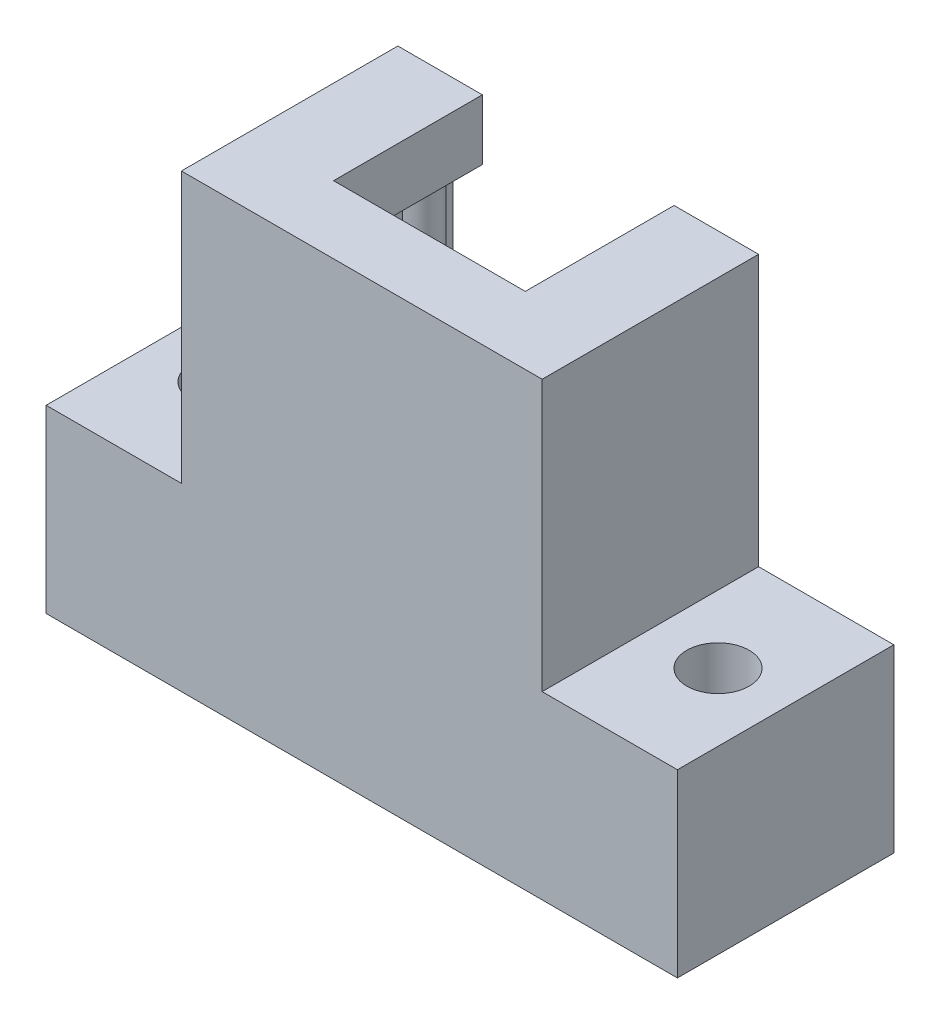
SolidWorks part; units mm, degrees
ref_plane "Front Plane" through (0, 0, 0) normal (0, 0, 1) x (1, 0, 0)
ref_plane "Top Plane" through (0, 0, 0) normal (0, 1, 0) x (1, 0, 0)
ref_plane "Right Plane" through (0, 0, 0) normal (1, 0, 0) x (0, 0, -1)
sketch "Sketch1" plane through (0, 0, 0) normal (0, 1, 0) x (1, 0, 0)
  line L1 (-17.5, -6) -> (17.5, -6)
  line L2 (-17.5, -6) -> (-17.5, 6)
  line L3 (-17.5, 6) -> (17.5, 6)
  line L4 (17.5, -6) -> (17.5, 6)
  line L5 (-17.5, -6) -> (17.5, 6) construction
  line L6 (-17.5, 6) -> (17.5, -6) construction
  point P0 (0, 0)
  dimension "D1" = 35
  dimension "D2" = 12
extrude "Boss-Extrude1" add sketch "Sketch1" along normal blind 10
sketch "Sketch2" plane through (0, 0, 0) normal (0, 1, 0) x (1, 0, 0)
  line L0 (17.5, 6) -> (-17.5, 6) construction
  line L1 (-10, -6) -> (10, -6)
  line L2 (-10, -6) -> (-10, 6)
  line L3 (-10, 6) -> (10, 6)
  line L4 (10, -6) -> (10, 6)
  line L5 (-10, -6) -> (10, 6) construction
  line L6 (-10, 6) -> (10, -6) construction
  point P0 (0, 0)
  dimension "D1" = 20
extrude "Boss-Extrude2" add sketch "Sketch2" along normal blind 25
sketch "Sketch3" plane through (0, 0, 0) normal (0, 1, 0) x (1, 0, 0)
  line L4 (-6.68, 2.615) -> (-6.68, -2.615)
  line L5 (-5.68, -3.615) -> (5.68, -3.615)
  line L6 (6.68, -2.615) -> (6.68, 2.615)
  line L7 (5.68, 3.615) -> (-5.68, 3.615)
  line L8 (-6.68, 2.615) -> (-6.68, -2.615)
  line L9 (-5.68, -3.615) -> (5.68, -3.615)
  line L10 (6.68, -2.615) -> (6.68, 2.615)
  line L11 (5.68, 3.615) -> (-5.68, 3.615)
  arc A4 (-6.68, -2.615) -> (-5.68, -3.615) centre (-5.68, -2.615) ccw
  arc A5 (5.68, -3.615) -> (6.68, -2.615) centre (5.68, -2.615) ccw
  arc A6 (6.68, 2.615) -> (5.68, 3.615) centre (5.68, 2.615) ccw
  arc A7 (-5.68, 3.615) -> (-6.68, 2.615) centre (-5.68, 2.615) ccw
  arc A8 (-6.68, -2.615) -> (-5.68, -3.615) centre (-5.68, -2.615) ccw
  arc A9 (5.68, -3.615) -> (6.68, -2.615) centre (5.68, -2.615) ccw
  arc A10 (6.68, 2.615) -> (5.68, 3.615) centre (5.68, 2.615) ccw
  arc A11 (-5.68, 3.615) -> (-6.68, 2.615) centre (-5.68, 2.615) ccw
  circle A36 centre (3.065, 0) radius 2.75 construction
  circle A37 centre (3.065, 0) radius 2.75
  circle A38 centre (-3.065, 0) radius 2.75 construction
  circle A39 centre (-3.065, 0) radius 2.75
  dimension "D1" = 0
sketch "Sketch5" plane through (0, 0, 0) normal (0, 1, 0) x (1, 0, 0)
  line L5 (6.93, 6) -> (6.93, -2.365)
  line L6 (17.5, 6) -> (-17.5, 6) construction
  line L7 (5.68, -3.615) -> (-5.68, -3.615)
  line L8 (-6.93, -2.365) -> (-6.93, 6)
  line L13 (-6.93, 6) -> (6.93, 6)
  line L14 (-6.68, 2.615) -> (-6.93, 2.615) construction
  line L15 (6.68, 2.615) -> (6.93, 2.615) construction
  arc A3 (6.93, -2.365) -> (5.68, -3.615) centre (5.68, -2.365) cw
  arc A4 (-5.68, -3.615) -> (-6.93, -2.365) centre (-5.68, -2.365) cw
  dimension "D1" = 0.25
extrude "Cut-Extrude1" cut sketch "Sketch5" along normal up to surface (21.65 mm away)
sketch "Sketch6" plane through (0, 25, 0) normal (0, 1, 0) x (1, 0, 0)
  line L0 (-5.315, 6) -> (-5.315, -2.25)
  line L1 (10, 6) -> (-10, 6) construction
  line L2 (-5.315, -2.25) -> (5.315, -2.25)
  line L3 (5.315, -2.25) -> (5.315, 6)
  line L4 (5.315, 6) -> (-5.315, 6)
  line L6 (-6.68, 2.615) -> (-5.315, 2.615) construction
  line L7 (5.315, -2.25) -> (5.315, -3.615) construction
  line L8 (-5.68, -3.615) -> (5.68, -3.615) construction
  line L9 (5.315, -2.25) -> (6.68, -2.25) construction
  line L10 (6.68, -2.615) -> (6.68, 2.615) construction
  line L11 (-4.815, 0) -> (-5.315, 0) construction
  circle A4 centre (-3.065, 0) radius 1.75 construction
  dimension "D1" = 0.5
  dimension "D2" = 3.5
extrude "Cut-Extrude2" cut sketch "Sketch6" against normal up to surface (3.35 mm away) up to face at (0, 21.65, 0.0796)
sketch "Sketch8" plane through (0, 0, 0) normal (0, -1, 0) x (1, 0, 0)
  line L0 (-6.93, -6) -> (-6.93, 2.365) construction
  line L1 (6.93, 2.365) -> (6.93, -6) construction
  line L2 (-6.68, -2.615) -> (-6.68, 2.615) construction
  circle A0 centre (-6.93, -4.1762) radius 1
  circle A1 centre (6.93, -4.1762) radius 1
  arc A2 (-6.68, -2.615) -> (-5.68, -3.615) centre (-5.68, -2.615) ccw construction
  arc A3 (5.68, -3.615) -> (6.68, -2.615) centre (5.68, -2.615) ccw construction
  point P14 (-5.93, -4.1762)
  dimension "D1" = 0.75
extrude "Boss-Extrude3" add sketch "Sketch8" against normal up to surface (21.65 mm away) up to face at (0, 21.65, -0.7022)
sketch "Sketch9" plane through (0, 7.21, 0) normal (0, -1, 0) x (1, 0, 0)
  line L1 (6.93, -5.425) -> (-6.93, -5.425)
  line L2 (6.93, -5.425) -> (6.93, 5.425)
  line L3 (6.93, 5.425) -> (-6.93, 5.425)
  line L4 (-6.93, -5.425) -> (-6.93, 5.425)
  line L7 (2.36, 4.925) -> (-2.36, 4.925) construction
  line L8 (2.36, 4.925) -> (-2.36, 4.925) construction
  line L9 (-5.37, -4.925) -> (-4.56, -4.925) construction
  line L10 (-5.37, -4.925) -> (-4.56, -4.925) construction
  line L11 (6.93, 2.365) -> (6.93, -3.1762) construction
  line L12 (-6.93, -3.1762) -> (-6.93, 2.365) construction
  dimension "D1" = 0.5
  dimension "D2" = 0.5
extrude "Cut-Extrude3" cut sketch "Sketch9" against normal blind 1.5 and the other way blind 0.5
ref_plane "Plane1" through (0, 5, 0) normal (0, -1, 0) x (-1, 0, 0)
sketch "Sketch10" plane through (0, 5, 0) normal (0, -1, 0) x (-1, 0, 0)
  line L0 (10, 6) -> (17.5, -6) construction
  line L1 (-15.28, -2.65) -> (-17.5, -2.65)
  line L2 (17.5, 6) -> (17.5, -6) construction
  line L3 (16.81, 0) -> (15.28, 2.65) construction
  line L4 (15.28, 2.65) -> (12.22, 2.65)
  line L5 (12.22, 2.65) -> (10.69, 0)
  line L6 (10.69, 0) -> (12.22, -2.65)
  line L7 (12.22, -2.65) -> (15.28, -2.65)
  line L8 (15.28, -2.65) -> (16.81, 0) construction
  line L9 (15.28, 2.65) -> (17.5, 2.65)
  line L11 (15.28, -2.65) -> (17.5, -2.65)
  line L12 (17.5, 2.65) -> (17.5, -2.65)
  line L13 (0, 0) -> (0, 8.3282) construction
  line L14 (-12.22, -2.65) -> (-15.28, -2.65)
  line L15 (-10.69, 0) -> (-12.22, -2.65)
  line L16 (-12.22, 2.65) -> (-10.69, 0)
  line L17 (-15.28, 2.65) -> (-12.22, 2.65)
  line L18 (-15.28, 2.65) -> (-17.5, 2.65)
  line L19 (-17.5, 2.65) -> (-17.5, -2.65)
  circle A0 centre (13.75, 0) radius 2.65 construction
  circle A1 centre (13.75, 0) radius 2.5 construction
  dimension "D1" = 5
  dimension "D2" = 0.15
extrude "Cut-Extrude4" [suppressed] cut sketch "Sketch10" against normal mid plane 2.5
hole_wizard "M2.5 Clearance Hole1" [suppressed] positions "Sketch13" profile "Sketch12" hole size "M2.5" standard "ANSI Metric"
sketch "Sketch13" plane through (0, 0, 0) normal (0, -1, 0) x (-1, 0, 0)
  line L0 (-13.75, 0) -> (13.75, 0) construction
  point P0 (13.75, 0)
  point P3 (-13.75, 0)
sketch "Sketch12" plane through (-13.75, 0, 0) normal (1, 0, 0) x (0, 0, -1)
  line L0 (0, 0) -> (0, 25)
  line L1 (0, 25) -> (1.45, 25)
  line L2 (1.45, 25) -> (1.45, 0)
  line L5 (1.45, 0) -> (0, 0)
  line L11 (0, -6.35) -> (0, 107.95) construction
  dimension "Thru Hole Dia." = 2.9
  dimension "Thru Hole Depth" = 25
hole_wizard "Tap Drill for #8-32 Tap1" positions "Sketch14" profile "Sketch15" hole size "#8-32" standard "ANSI Inch" end condition through all
sketch "Sketch14" plane through (0, 10, 0) normal (0, 1, 0) x (1, 0, 0)
  line L1 (0, 0) -> (0, 9.7365) construction
  point P0 (-13.75, 0)
  point P10 (13.75, 0)
sketch "Sketch15" plane through (-13.75, 10, 0) normal (1, 0, 0) x (0, 0, 1)
  line L0 (0, 0) -> (0, 10)
  line L1 (0, 10) -> (1.7272, 10)
  line L2 (1.7272, 10) -> (1.7272, 0)
  line L5 (1.7272, 0) -> (0, 0)
  line L11 (0, -6.35) -> (0, 107.95) construction
  dimension "Thru Hole Dia." = 3.4544
  dimension "Thru Hole Depth" = 10
